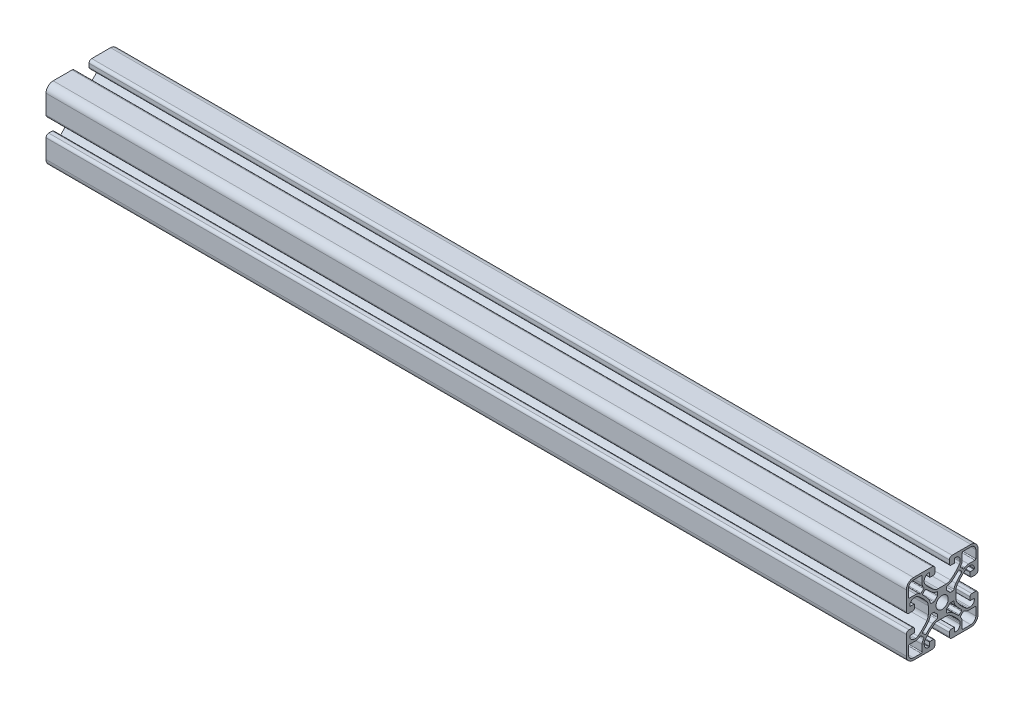
SolidWorks part; units mm, degrees
ref_plane "Front Plane" through (0, 0, 0) normal (1, 0, 0) x (0, 1, 0)
ref_plane "Top Plane" through (0, 0, 0) normal (0, 0, 1) x (0, 1, 0)
ref_plane "Right Plane" through (0, 0, 0) normal (0, 1, 0) x (-1, 0, 0)
sketch "Sketch1" plane through (0, 0, 0) normal (1, 0, 0) x (0, 1, 0)
  line L0 (9.8448, 4.6378) -> (10.0126, 4.8558)
  line L1 (10.4243, 6.082) -> (10.4243, 8.3868)
  line L2 (10.7418, 8.7043) -> (13.4723, 8.7043)
  line L3 (15.2503, 6.9263) -> (15.2503, 4.1958)
  line L4 (14.9328, 3.8783) -> (12.628, 3.8783)
  line L5 (11.4018, 3.4666) -> (11.1838, 3.2989)
  line L6 (10.7635, 3.3243) -> (9.8703, 4.2176)
  line L7 (-4.559, 3.2986) -> (-4.7769, 3.4664)
  line L8 (-6.0032, 3.8781) -> (-8.308, 3.8781)
  line L9 (-8.6255, 4.1956) -> (-8.6255, 6.9261)
  line L10 (-6.8475, 8.7041) -> (-4.117, 8.7041)
  line L11 (-3.7995, 8.3866) -> (-3.7995, 6.0818)
  line L12 (-3.3878, 4.8556) -> (-3.22, 4.6376)
  line L13 (-3.2454, 4.2174) -> (-4.1387, 3.3241)
  line L14 (4.9, -0.3064) -> (4.9, 0.6387)
  line L15 (9.4106, 3.5999) -> (10.1461, 2.8644)
  line L16 (7.1849, -1.6462) -> (6.2397, -1.6462)
  line L17 (0.3853, -1.6462) -> (-0.5599, -1.6462)
  line L18 (-3.521, 2.8644) -> (-2.7855, 3.5999)
  line L19 (1.725, 0.6387) -> (1.725, -0.3064)
  line L20 (-3.2198, -11.1051) -> (-3.3876, -11.3231)
  line L21 (-3.7993, -12.5493) -> (-3.7993, -14.8542)
  line L22 (-4.1168, -15.1717) -> (-6.8473, -15.1717)
  line L23 (-8.6253, -13.3937) -> (-8.6253, -10.6632)
  line L24 (-8.3078, -10.3457) -> (-6.0029, -10.3457)
  line L25 (-4.7767, -9.934) -> (-4.5588, -9.7662)
  line L26 (-4.1385, -9.7916) -> (-3.2452, -10.6849)
  line L27 (11.184, -9.7659) -> (11.402, -9.9337)
  line L28 (12.6282, -10.3454) -> (14.933, -10.3454)
  line L29 (15.2505, -10.6629) -> (15.2505, -13.3934)
  line L30 (13.4725, -15.1714) -> (10.742, -15.1714)
  line L31 (10.4245, -14.8539) -> (10.4245, -12.5491)
  line L32 (10.0128, -11.3229) -> (9.845, -11.1049)
  line L33 (9.8705, -10.6847) -> (10.7638, -9.7914)
  line L34 (1.725, -6.1609) -> (1.725, -7.106)
  line L35 (-2.7855, -10.0672) -> (-3.521, -9.3317)
  line L36 (-0.5599, -4.8212) -> (0.3853, -4.8212)
  line L37 (6.2397, -4.8212) -> (7.1849, -4.8212)
  line L38 (10.1461, -9.3317) -> (9.4106, -10.0672)
  line L39 (4.9, -7.106) -> (4.9, -6.1609)
  line L40 (0.7725, -13.7112) -> (0.7725, -14.9812)
  line L41 (-0.9737, -13.0762) -> (0.1375, -13.0762)
  line L42 (-1.1325, -14.5049) -> (-1.1325, -13.2349)
  line L43 (-1.45, -14.6637) -> (-1.2912, -14.6637)
  line L44 (-3.0375, -12.5811) -> (-3.0375, -13.0762)
  line L45 (4.7051, -8.1549) -> (1.9199, -8.1549)
  line L46 (9.6625, -13.0762) -> (9.6625, -12.5811)
  line L47 (7.9163, -14.6637) -> (8.075, -14.6637)
  line L48 (7.7575, -13.2349) -> (7.7575, -14.5049)
  line L49 (6.4875, -13.0762) -> (7.5988, -13.0762)
  line L50 (5.8525, -14.9812) -> (5.8525, -13.7112)
  line L51 (13.4725, -15.9337) -> (6.805, -15.9337)
  line L52 (16.0125, -6.7262) -> (16.0125, -13.3937)
  line L53 (13.79, -5.7737) -> (15.06, -5.7737)
  line L54 (13.155, -7.5199) -> (13.155, -6.4087)
  line L55 (14.5838, -7.6787) -> (13.3138, -7.6787)
  line L56 (14.7425, -7.9962) -> (14.7425, -7.8374)
  line L57 (12.6599, -9.5837) -> (13.155, -9.5837)
  line L58 (8.2338, -1.8411) -> (8.2338, -4.6262)
  line L59 (13.155, 3.1163) -> (12.6599, 3.1163)
  line L60 (14.7425, 1.3701) -> (14.7425, 1.5288)
  line L61 (13.3138, 1.2113) -> (14.5838, 1.2113)
  line L62 (13.155, -0.0587) -> (13.155, 1.0526)
  line L63 (15.06, -0.6937) -> (13.79, -0.6937)
  line L64 (16.0125, 6.9263) -> (16.0125, 0.2588)
  line L65 (6.805, 9.4663) -> (13.4725, 9.4663)
  line L66 (5.8525, 7.2438) -> (5.8525, 8.5138)
  line L67 (7.5988, 6.6088) -> (6.4875, 6.6088)
  line L68 (7.7575, 8.0376) -> (7.7575, 6.7676)
  line L69 (8.075, 8.1963) -> (7.9163, 8.1963)
  line L70 (9.6625, 6.1138) -> (9.6625, 6.6088)
  line L71 (1.9199, 1.6876) -> (4.7051, 1.6876)
  line L72 (-3.0375, 6.6088) -> (-3.0375, 6.1138)
  line L73 (-1.2912, 8.1963) -> (-1.45, 8.1963)
  line L74 (-1.1325, 6.7676) -> (-1.1325, 8.0376)
  line L75 (0.1375, 6.6088) -> (-0.9737, 6.6088)
  line L76 (0.7725, 8.5138) -> (0.7725, 7.2438)
  line L77 (-6.8475, 9.4663) -> (-0.18, 9.4663)
  line L78 (-9.3875, 0.2588) -> (-9.3875, 6.9263)
  line L79 (-7.165, -0.6937) -> (-8.435, -0.6937)
  line L80 (-6.53, 1.0526) -> (-6.53, -0.0587)
  line L81 (-7.9587, 1.2113) -> (-6.6887, 1.2113)
  line L82 (-8.1175, 1.5288) -> (-8.1175, 1.3701)
  line L83 (-6.0349, 3.1163) -> (-6.53, 3.1163)
  line L84 (-1.6087, -4.6262) -> (-1.6087, -1.8411)
  line L85 (-6.53, -9.5837) -> (-6.0349, -9.5837)
  line L86 (-8.1175, -7.8374) -> (-8.1175, -7.9962)
  line L87 (-6.6887, -7.6787) -> (-7.9587, -7.6787)
  line L88 (-6.53, -6.4087) -> (-6.53, -7.5199)
  line L89 (-8.435, -5.7737) -> (-7.165, -5.7737)
  line L90 (-9.3875, -13.3937) -> (-9.3875, -6.7262)
  line L91 (-0.18, -15.9337) -> (-6.8475, -15.9337)
  arc A0 (9.8448, 4.6378) -> (9.8703, 4.2176) centre (10.0948, 4.4421) ccw
  arc A1 (10.0126, 4.8558) -> (10.4243, 6.082) centre (8.3923, 6.082) ccw
  arc A2 (10.7418, 8.7043) -> (10.4243, 8.3868) centre (10.7418, 8.3868) ccw
  arc A3 (15.2503, 6.9263) -> (13.4723, 8.7043) centre (13.4723, 6.9263) ccw
  arc A4 (14.9328, 3.8783) -> (15.2503, 4.1958) centre (14.9328, 4.1958) ccw
  arc A5 (12.628, 3.8783) -> (11.4018, 3.4666) centre (12.628, 1.8463) ccw
  arc A6 (10.7635, 3.3243) -> (11.1838, 3.2989) centre (10.988, 3.5488) ccw
  arc A7 (-4.559, 3.2986) -> (-4.1387, 3.3241) centre (-4.3632, 3.5486) ccw
  arc A8 (-4.7769, 3.4664) -> (-6.0032, 3.8781) centre (-6.0032, 1.8461) ccw
  arc A9 (-8.6255, 4.1956) -> (-8.308, 3.8781) centre (-8.308, 4.1956) ccw
  arc A10 (-6.8475, 8.7041) -> (-8.6255, 6.9261) centre (-6.8475, 6.9261) ccw
  arc A11 (-3.7995, 8.3866) -> (-4.117, 8.7041) centre (-4.117, 8.3866) ccw
  arc A12 (-3.7995, 6.0818) -> (-3.3878, 4.8556) centre (-1.7675, 6.0818) ccw
  arc A13 (-3.2454, 4.2174) -> (-3.22, 4.6376) centre (-3.47, 4.4419) ccw
  arc A14 (5.9736, -1.5018) -> (6.2397, -1.6462) centre (6.2397, -1.3287) ccw
  arc A15 (5.9736, -1.5018) -> (5.0443, -0.5726) centre (3.3125, -3.2337) ccw
  arc A16 (4.9, -0.3064) -> (5.0443, -0.5726) centre (5.2175, -0.3064) ccw
  arc A17 (5.1763, 0.9535) -> (4.9, 0.6387) centre (5.2175, 0.6387) ccw
  arc A18 (5.1763, 0.9535) -> (6.7288, 1.586) centre (4.7476, 4.2276) ccw
  arc A19 (6.7288, 1.586) -> (8.9531, 3.5911) centre (-3.2534, 14.8956) ccw
  arc A20 (9.4106, 3.5999) -> (8.9531, 3.5911) centre (9.1861, 3.3754) ccw
  arc A21 (10.1373, 2.4069) -> (10.1461, 2.8644) centre (9.9215, 2.6399) ccw
  arc A22 (10.1373, 2.4069) -> (8.1322, 0.1826) centre (21.4418, -9.7996) ccw
  arc A23 (8.1322, 0.1826) -> (7.4997, -1.3699) centre (10.7738, -1.7986) ccw
  arc A24 (7.1849, -1.6462) -> (7.4997, -1.3699) centre (7.1849, -1.3287) ccw
  arc A25 (1.5807, -0.5726) -> (1.725, -0.3064) centre (1.4075, -0.3064) ccw
  arc A26 (1.5807, -0.5726) -> (0.6514, -1.5018) centre (3.3125, -3.2337) ccw
  arc A27 (0.3853, -1.6462) -> (0.6514, -1.5018) centre (0.3853, -1.3287) ccw
  arc A28 (-0.8747, -1.3699) -> (-0.5599, -1.6462) centre (-0.5599, -1.3287) ccw
  arc A29 (-0.8747, -1.3699) -> (-1.5071, 0.1826) centre (-4.1487, -1.7986) ccw
  arc A30 (-1.5071, 0.1826) -> (-3.5122, 2.4069) centre (-14.8167, -9.7996) ccw
  arc A31 (-3.521, 2.8644) -> (-3.5122, 2.4069) centre (-3.2965, 2.6399) ccw
  arc A32 (-2.3281, 3.5911) -> (-2.7855, 3.5999) centre (-2.561, 3.3754) ccw
  arc A33 (-2.3281, 3.5911) -> (-0.1038, 1.586) centre (9.8784, 14.8956) ccw
  arc A34 (-0.1038, 1.586) -> (1.4487, 0.9535) centre (1.8774, 4.2276) ccw
  arc A35 (1.725, 0.6387) -> (1.4487, 0.9535) centre (1.4075, 0.6387) ccw
  arc A36 (-3.2198, -11.1051) -> (-3.2452, -10.6849) centre (-3.4697, -10.9094) ccw
  arc A37 (-3.3876, -11.3231) -> (-3.7993, -12.5493) centre (-1.7673, -12.5493) ccw
  arc A38 (-4.1168, -15.1717) -> (-3.7993, -14.8542) centre (-4.1168, -14.8542) ccw
  arc A39 (-8.6253, -13.3937) -> (-6.8473, -15.1717) centre (-6.8473, -13.3937) ccw
  arc A40 (-8.3078, -10.3457) -> (-8.6253, -10.6632) centre (-8.3078, -10.6632) ccw
  arc A41 (-6.0029, -10.3457) -> (-4.7767, -9.934) centre (-6.0029, -8.3137) ccw
  arc A42 (-4.1385, -9.7916) -> (-4.5588, -9.7662) centre (-4.363, -10.0161) ccw
  arc A43 (11.184, -9.7659) -> (10.7638, -9.7914) centre (10.9883, -10.0159) ccw
  arc A44 (11.402, -9.9337) -> (12.6282, -10.3454) centre (12.6282, -8.3134) ccw
  arc A45 (15.2505, -10.6629) -> (14.933, -10.3454) centre (14.933, -10.6629) ccw
  arc A46 (13.4725, -15.1714) -> (15.2505, -13.3934) centre (13.4725, -13.3934) ccw
  arc A47 (10.4245, -14.8539) -> (10.742, -15.1714) centre (10.742, -14.8539) ccw
  arc A48 (10.4245, -12.5491) -> (10.0128, -11.3229) centre (8.3925, -12.5491) ccw
  arc A49 (9.8705, -10.6847) -> (9.845, -11.1049) centre (10.095, -10.9092) ccw
  arc A50 (0.6514, -4.9655) -> (0.3853, -4.8212) centre (0.3853, -5.1387) ccw
  arc A51 (0.6514, -4.9655) -> (1.5807, -5.8947) centre (3.3125, -3.2337) ccw
  arc A52 (1.725, -6.1609) -> (1.5807, -5.8947) centre (1.4075, -6.1609) ccw
  arc A53 (1.4487, -7.4208) -> (1.725, -7.106) centre (1.4075, -7.106) ccw
  arc A54 (1.4487, -7.4208) -> (-0.1038, -8.0533) centre (1.8774, -10.6949) ccw
  arc A55 (-0.1038, -8.0533) -> (-2.3281, -10.0584) centre (9.8784, -21.3629) ccw
  arc A56 (-2.7855, -10.0672) -> (-2.3281, -10.0584) centre (-2.561, -9.8427) ccw
  arc A57 (-3.5122, -8.8742) -> (-3.521, -9.3317) centre (-3.2965, -9.1072) ccw
  arc A58 (-3.5122, -8.8742) -> (-1.5071, -6.65) centre (-14.8167, 3.3322) ccw
  arc A59 (-1.5071, -6.65) -> (-0.8747, -5.0974) centre (-4.1487, -4.6688) ccw
  arc A60 (-0.5599, -4.8212) -> (-0.8747, -5.0974) centre (-0.5599, -5.1387) ccw
  arc A61 (5.0443, -5.8947) -> (4.9, -6.1609) centre (5.2175, -6.1609) ccw
  arc A62 (5.0443, -5.8947) -> (5.9736, -4.9655) centre (3.3125, -3.2337) ccw
  arc A63 (6.2397, -4.8212) -> (5.9736, -4.9655) centre (6.2397, -5.1387) ccw
  arc A64 (7.4997, -5.0974) -> (7.1849, -4.8212) centre (7.1849, -5.1387) ccw
  arc A65 (7.4997, -5.0974) -> (8.1322, -6.65) centre (10.7738, -4.6688) ccw
  arc A66 (8.1322, -6.65) -> (10.1373, -8.8742) centre (21.4418, 3.3322) ccw
  arc A67 (10.1461, -9.3317) -> (10.1373, -8.8742) centre (9.9215, -9.1072) ccw
  arc A68 (8.9531, -10.0584) -> (9.4106, -10.0672) centre (9.1861, -9.8427) ccw
  arc A69 (8.9531, -10.0584) -> (6.7288, -8.0533) centre (-3.2534, -21.3629) ccw
  arc A70 (6.7288, -8.0533) -> (5.1763, -7.4208) centre (4.7476, -10.6949) ccw
  arc A71 (4.9, -7.106) -> (5.1763, -7.4208) centre (5.2175, -7.106) ccw
  circle A72 centre (3.3125, -3.2337) radius 2.159
  arc A73 (-0.18, -15.9337) -> (0.7725, -14.9812) centre (-0.18, -14.9812) ccw
  arc A74 (0.7725, -13.7112) -> (0.1375, -13.0762) centre (0.1375, -13.7112) ccw
  arc A75 (-0.9737, -13.0762) -> (-1.1325, -13.2349) centre (-0.9737, -13.2349) ccw
  arc A76 (-1.2912, -14.6637) -> (-1.1325, -14.5049) centre (-1.2912, -14.5049) ccw
  arc A77 (-3.0375, -13.0762) -> (-1.45, -14.6637) centre (-1.45, -13.0762) ccw
  arc A78 (-2.7802, -11.8147) -> (-3.0375, -12.5811) centre (-1.7675, -12.5811) ccw
  arc A79 (0.404, -8.6569) -> (-2.7802, -11.8147) centre (9.8784, -21.3947) ccw
  arc A80 (1.9199, -8.1549) -> (0.404, -8.6569) centre (1.9199, -10.6949) ccw
  arc A81 (6.221, -8.6569) -> (4.7051, -8.1549) centre (4.7051, -10.6949) ccw
  arc A82 (9.4052, -11.8147) -> (6.221, -8.6569) centre (-3.2534, -21.3947) ccw
  arc A83 (9.6625, -12.5811) -> (9.4052, -11.8147) centre (8.3925, -12.5811) ccw
  arc A84 (8.075, -14.6637) -> (9.6625, -13.0762) centre (8.075, -13.0762) ccw
  arc A85 (7.7575, -14.5049) -> (7.9163, -14.6637) centre (7.9163, -14.5049) ccw
  arc A86 (7.7575, -13.2349) -> (7.5988, -13.0762) centre (7.5988, -13.2349) ccw
  arc A87 (6.4875, -13.0762) -> (5.8525, -13.7112) centre (6.4875, -13.7112) ccw
  arc A88 (5.8525, -14.9812) -> (6.805, -15.9337) centre (6.805, -14.9812) ccw
  arc A89 (13.4725, -15.9337) -> (16.0125, -13.3937) centre (13.4725, -13.3937) ccw
  arc A90 (16.0125, -6.7262) -> (15.06, -5.7737) centre (15.06, -6.7262) ccw
  arc A91 (13.79, -5.7737) -> (13.155, -6.4087) centre (13.79, -6.4087) ccw
  arc A92 (13.155, -7.5199) -> (13.3138, -7.6787) centre (13.3138, -7.5199) ccw
  arc A93 (14.7425, -7.8374) -> (14.5838, -7.6787) centre (14.5838, -7.8374) ccw
  arc A94 (13.155, -9.5837) -> (14.7425, -7.9962) centre (13.155, -7.9962) ccw
  arc A95 (11.8936, -9.3263) -> (12.6599, -9.5837) centre (12.6599, -8.3137) ccw
  arc A96 (8.7357, -6.1421) -> (11.8936, -9.3263) centre (21.4735, 3.3322) ccw
  arc A97 (8.2338, -4.6262) -> (8.7357, -6.1421) centre (10.7738, -4.6262) ccw
  arc A98 (8.7357, -0.3252) -> (8.2338, -1.8411) centre (10.7738, -1.8411) ccw
  arc A99 (11.8936, 2.859) -> (8.7357, -0.3252) centre (21.4735, -9.7996) ccw
  arc A100 (12.6599, 3.1163) -> (11.8936, 2.859) centre (12.6599, 1.8463) ccw
  arc A101 (14.7425, 1.5288) -> (13.155, 3.1163) centre (13.155, 1.5288) ccw
  arc A102 (14.5838, 1.2113) -> (14.7425, 1.3701) centre (14.5838, 1.3701) ccw
  arc A103 (13.3138, 1.2113) -> (13.155, 1.0526) centre (13.3138, 1.0526) ccw
  arc A104 (13.155, -0.0587) -> (13.79, -0.6937) centre (13.79, -0.0587) ccw
  arc A105 (15.06, -0.6937) -> (16.0125, 0.2588) centre (15.06, 0.2588) ccw
  arc A106 (16.0125, 6.9263) -> (13.4725, 9.4663) centre (13.4725, 6.9263) ccw
  arc A107 (6.805, 9.4663) -> (5.8525, 8.5138) centre (6.805, 8.5138) ccw
  arc A108 (5.8525, 7.2438) -> (6.4875, 6.6088) centre (6.4875, 7.2438) ccw
  arc A109 (7.5988, 6.6088) -> (7.7575, 6.7676) centre (7.5988, 6.7676) ccw
  arc A110 (7.9163, 8.1963) -> (7.7575, 8.0376) centre (7.9163, 8.0376) ccw
  arc A111 (9.6625, 6.6088) -> (8.075, 8.1963) centre (8.075, 6.6088) ccw
  arc A112 (9.4052, 5.3474) -> (9.6625, 6.1138) centre (8.3925, 6.1138) ccw
  arc A113 (6.221, 2.1896) -> (9.4052, 5.3474) centre (-3.2534, 14.9273) ccw
  arc A114 (4.7051, 1.6876) -> (6.221, 2.1896) centre (4.7051, 4.2276) ccw
  arc A115 (0.404, 2.1896) -> (1.9199, 1.6876) centre (1.9199, 4.2276) ccw
  arc A116 (-2.7802, 5.3474) -> (0.404, 2.1896) centre (9.8784, 14.9273) ccw
  arc A117 (-3.0375, 6.1138) -> (-2.7802, 5.3474) centre (-1.7675, 6.1138) ccw
  arc A118 (-1.45, 8.1963) -> (-3.0375, 6.6088) centre (-1.45, 6.6088) ccw
  arc A119 (-1.1325, 8.0376) -> (-1.2912, 8.1963) centre (-1.2912, 8.0376) ccw
  arc A120 (-1.1325, 6.7676) -> (-0.9737, 6.6088) centre (-0.9737, 6.7676) ccw
  arc A121 (0.1375, 6.6088) -> (0.7725, 7.2438) centre (0.1375, 7.2438) ccw
  arc A122 (0.7725, 8.5138) -> (-0.18, 9.4663) centre (-0.18, 8.5138) ccw
  arc A123 (-6.8475, 9.4663) -> (-9.3875, 6.9263) centre (-6.8475, 6.9263) ccw
  arc A124 (-9.3875, 0.2588) -> (-8.435, -0.6937) centre (-8.435, 0.2588) ccw
  arc A125 (-7.165, -0.6937) -> (-6.53, -0.0587) centre (-7.165, -0.0587) ccw
  arc A126 (-6.53, 1.0526) -> (-6.6887, 1.2113) centre (-6.6887, 1.0526) ccw
  arc A127 (-8.1175, 1.3701) -> (-7.9587, 1.2113) centre (-7.9587, 1.3701) ccw
  arc A128 (-6.53, 3.1163) -> (-8.1175, 1.5288) centre (-6.53, 1.5288) ccw
  arc A129 (-5.2685, 2.859) -> (-6.0349, 3.1163) centre (-6.0349, 1.8463) ccw
  arc A130 (-2.1107, -0.3252) -> (-5.2685, 2.859) centre (-14.8485, -9.7996) ccw
  arc A131 (-1.6087, -1.8411) -> (-2.1107, -0.3252) centre (-4.1487, -1.8411) ccw
  arc A132 (-2.1107, -6.1421) -> (-1.6087, -4.6262) centre (-4.1487, -4.6262) ccw
  arc A133 (-5.2685, -9.3263) -> (-2.1107, -6.1421) centre (-14.8485, 3.3322) ccw
  arc A134 (-6.0349, -9.5837) -> (-5.2685, -9.3263) centre (-6.0349, -8.3137) ccw
  arc A135 (-8.1175, -7.9962) -> (-6.53, -9.5837) centre (-6.53, -7.9962) ccw
  arc A136 (-7.9587, -7.6787) -> (-8.1175, -7.8374) centre (-7.9587, -7.8374) ccw
  arc A137 (-6.6887, -7.6787) -> (-6.53, -7.5199) centre (-6.6887, -7.5199) ccw
  arc A138 (-6.53, -6.4087) -> (-7.165, -5.7737) centre (-7.165, -6.4087) ccw
  arc A139 (-8.435, -5.7737) -> (-9.3875, -6.7262) centre (-8.435, -6.7262) ccw
  arc A140 (-9.3875, -13.3937) -> (-6.8475, -15.9337) centre (-6.8475, -13.3937) ccw
  dimension "D1" = 25.4
extrude "Boss-Extrude1" add sketch "Sketch1" along normal blind 304.8
